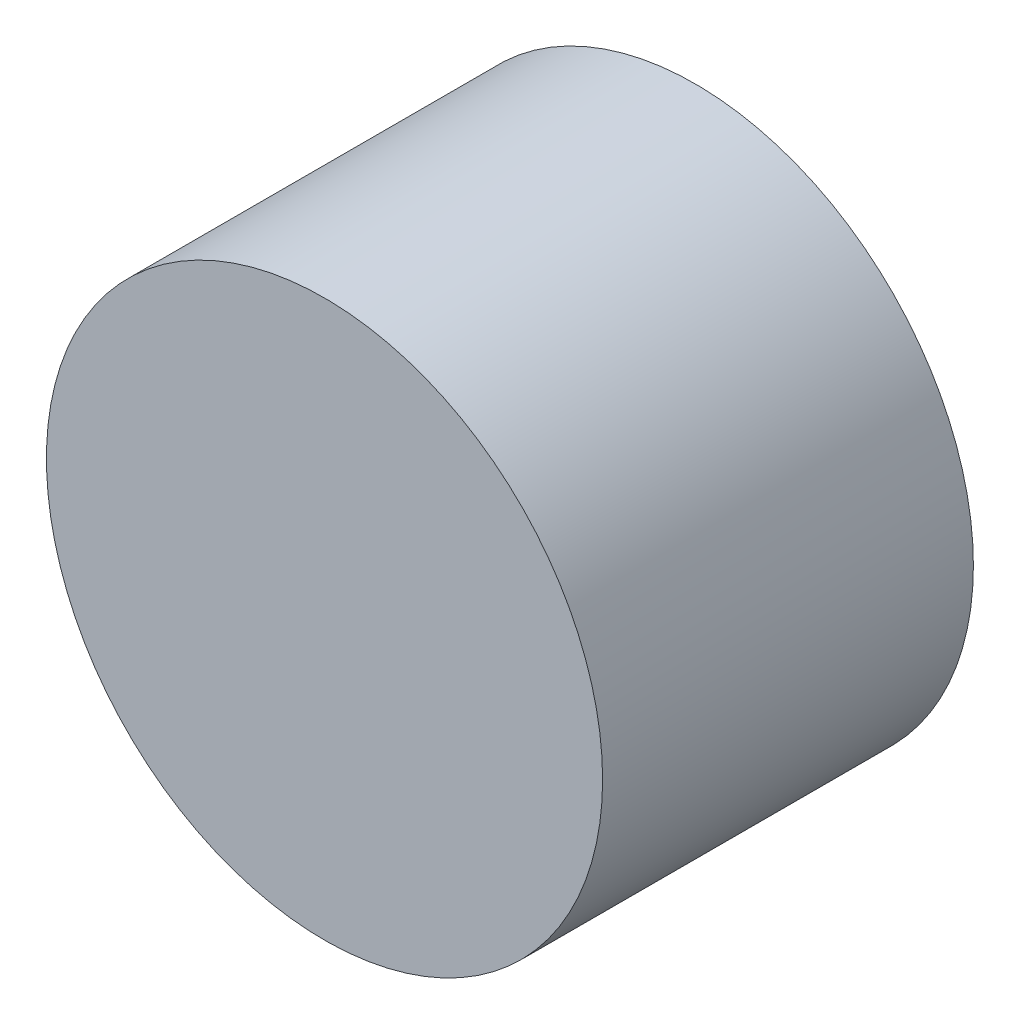
SolidWorks part; units mm, degrees
material "1.4000 (X6Cr13)"
ref_plane "Plan de face" through (0, 0, 0) normal (0, 0, 1) x (1, 0, 0)
ref_plane "Plan de dessus" through (0, 0, 0) normal (0, 1, 0) x (1, 0, 0)
ref_plane "Plan de droite" through (0, 0, 0) normal (1, 0, 0) x (0, 0, -1)
sketch "Esquisse1" plane through (0, 0, 0) normal (0, 0, 1) x (1, 0, 0)
  circle A0 centre (0, 0) radius 1.5
extrude "Boss.-Extru.1" add sketch "Esquisse1" along normal blind 2
